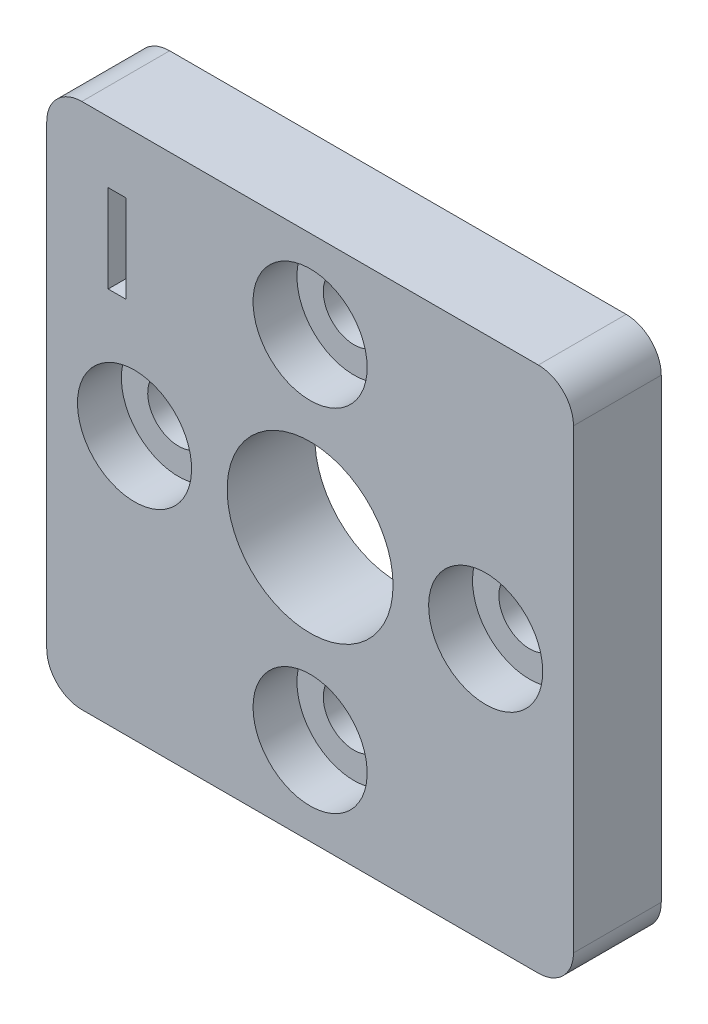
SolidWorks part; units mm, degrees
ref_plane "Front Plane" through (0, 0, 0) normal (0, 0, 1) x (1, 0, 0)
ref_plane "Top Plane" through (0, 0, 0) normal (0, 1, 0) x (1, 0, 0)
ref_plane "Right Plane" through (0, 0, 0) normal (1, 0, 0) x (0, 0, -1)
sketch "Sketch1" plane through (0, 0, 0) normal (0, 0, 1) x (1, 0, 0)
  line L1 (15, -15) -> (-15, -15)
  line L2 (15, -15) -> (15, 15)
  line L3 (15, 15) -> (-15, 15)
  line L4 (-15, -15) -> (-15, 15)
  line L5 (15, -15) -> (-15, 15) construction
  line L6 (15, 15) -> (-15, -15) construction
  circle A0 centre (0, 0) radius 4.725
  point P0 (0, 0)
  dimension "D3" = 9.45
  dimension "D1" = 30
  dimension "D2" = 30
extrude "Boss-Extrude1" add sketch "Sketch1" along normal blind 5
fillet "Fillet1" radius 2 4 edges at (-15, -15, 2.5) (15, -15, 2.5) (-15, 15, 2.5) (15, 15, 2.5)
sketch "Sketch2" plane through (0, 0, 0) normal (0, 0, 1) x (1, 0, 0)
  line L0 (0, 13.7372) -> (0, -14.3307) construction
  circle A1 centre (0, 10) radius 1.75
  dimension "D1" = 3.5
  dimension "D2" = 10
extrude "Cut-Extrude1" cut sketch "Sketch2" along normal through all both
pattern_circular "CirPattern1" count 4 over 360 about axis through (0, 0, 0) along (0, 0, 1) of "Cut-Extrude1"
ref_plane "Plane1" through (0, 0, 5) normal (0, 0, 1) x (1, 0, 0)
sketch "Sketch3" plane through (0, 0, 5) normal (0, 0, 1) x (1, 0, 0)
  circle A0 centre (0, 10) radius 3.25
  dimension "D1" = 6.5
extrude "Cut-Extrude2" cut sketch "Sketch3" against normal blind 2.5
pattern_circular "CirPattern2" count 4 over 360 about axis through (0, 0, 0) along (0, 0, 1) of "Cut-Extrude2"
sketch "Sketch4" plane through (0, 0, 5) normal (0, 0, 1) x (1, 0, 0)
  line L1 (-11.5, 11.5) -> (-10.5, 11.5)
  line L2 (-11.5, 11.5) -> (-11.5, 6.5)
  line L3 (-11.5, 6.5) -> (-10.5, 6.5)
  line L4 (-10.5, 11.5) -> (-10.5, 6.5)
  line L5 (-11.5, 11.5) -> (-10.5, 6.5) construction
  line L6 (-11.5, 6.5) -> (-10.5, 11.5) construction
  point P0 (-11, 9)
  dimension "D1" = 1
  dimension "D2" = 5
  dimension "D3" = 9
  dimension "D4" = 11
extrude "Cut-Extrude3" cut sketch "Sketch4" against normal blind 2.5
